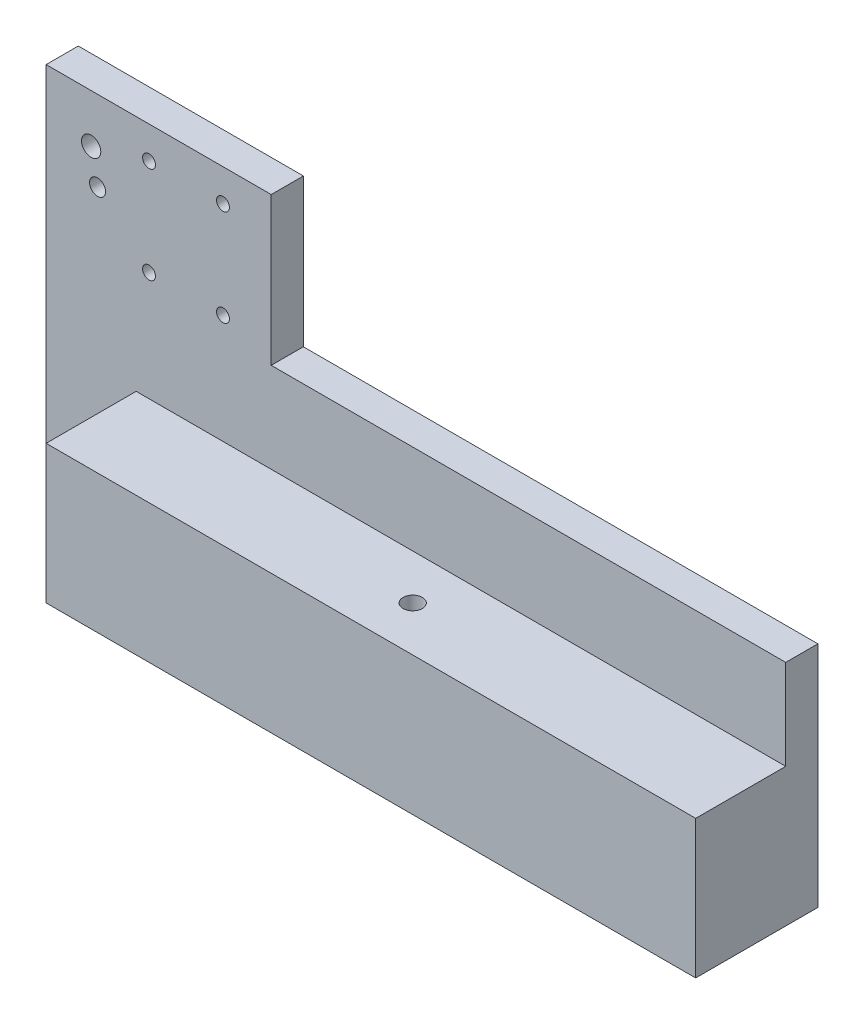
SolidWorks part; units mm, degrees
ref_plane "Ön Düzlem" through (0, 0, 0) normal (0, 0, 1) x (1, 0, 0)
ref_plane "Üst Düzlem" through (0, 0, 0) normal (0, 1, 0) x (1, 0, 0)
ref_plane "Sağ Düzlem" through (0, 0, 0) normal (1, 0, 0) x (0, 0, -1)
sketch "Sketch2" plane through (0, 0, 0) normal (0, 0, 1) x (1, 0, 0)
  line L1 (0, 0) -> (230, 0)
  line L2 (0, 0) -> (0, -120)
  line L3 (0, -120) -> (230, -120)
  line L4 (230, 0) -> (230, -120)
  dimension "D1" = 230
  dimension "D2" = 120
extrude "Boss-Extrude1" add sketch "Sketch2" along normal blind 38
sketch "Sketch3" plane through (0, 0, 38) normal (0, 0, 1) x (1, 0, 0)
  line L0 (28, -120) -> (28, -74)
  line L1 (0, -120) -> (230, -120) construction
  line L2 (28, -74) -> (230, -74)
  line L3 (230, -120) -> (230, 0) construction
  line L5 (0, 0) -> (230, 0)
  line L6 (0, 0) -> (0, -120)
  line L7 (0, -120) -> (28, -120)
  line L8 (230, 0) -> (230, -74)
  dimension "D1" = 46
  dimension "D2" = 28
extrude "Cut-Extrude1" cut sketch "Sketch3" against normal blind 28
sketch "Sketch4" plane through (0, 0, 10) normal (0, 0, 1) x (1, 0, 0)
  line L0 (28, -74) -> (230, -74) construction
  line L1 (230, 0) -> (70, 0)
  line L2 (230, 0) -> (230, -46)
  line L3 (230, -46) -> (70, -46)
  line L4 (70, 0) -> (70, -46)
  line L5 (230, -120) -> (230, -74) construction
  dimension "D1" = 28
  dimension "D2" = 160
extrude "Cut-Extrude2" cut sketch "Sketch4" against normal through all
sketch "Sketch5" plane through (0, 0, 38) normal (0, 0, 1) x (1, 0, 0)
  line L0 (70, 0) -> (0, 0) construction
  line L1 (-45.2028, -117) -> (266.6205, -117)
  line L2 (-45.2028, -117) -> (-45.2028, -145.846)
  line L3 (-45.2028, -145.846) -> (266.6205, -145.846)
  line L4 (266.6205, -117) -> (266.6205, -145.846)
  dimension "D1" = 117
extrude "Cut-Extrude3" cut sketch "Sketch5" against normal blind 72
sketch "Sketch6" plane through (0, -74, 0) normal (0, 1, 0) x (1, 0, 0)
  line L0 (28, -38) -> (230, -38) construction
  line L1 (28, -10) -> (28, -38) construction
  circle A0 centre (128, -24) radius 3
  dimension "D3" = 6
  dimension "D1" = 14
  dimension "D2" = 100
extrude "Cut-Extrude4" cut sketch "Sketch6" against normal blind 15
sketch "Sketch7" plane through (0, 0, 10) normal (0, 0, 1) x (1, 0, 0)
  line L0 (70, 0) -> (0, 0) construction
  line L1 (28, -117) -> (0, -117) construction
  line L2 (0, 0) -> (0, -117) construction
  circle A0 centre (14, -15) radius 3
  circle A1 centre (14, -102) radius 3
  dimension "D2" = 6
  dimension "D3" = 6
  dimension "D5" = 14
  dimension "D1" = 15
  dimension "D4" = 15
  dimension "D6" = 14
extrude "Cut-Extrude5" cut sketch "Sketch7" against normal through all
sketch "Sketch8" plane through (0, 0, 0) normal (0, 0, -1) x (-1, 0, 0)
  line L0 (-70, 0) -> (0, 0) construction
  line L1 (-32, -40) -> (-55, -40) construction
  line L2 (-32, -40) -> (-32, -10) construction
  line L3 (-32, -10) -> (-55, -10) construction
  line L4 (-55, -40) -> (-55, -10) construction
  line L5 (-32, -40) -> (-55, -10) construction
  line L6 (-32, -10) -> (-55, -40) construction
  line L7 (0, 0) -> (0, -117) construction
  circle A0 centre (-55, -10) radius 2
  circle A1 centre (-55, -40) radius 2
  circle A2 centre (-32, -40) radius 2
  circle A3 centre (-32, -10) radius 2
  point P0 (-43.5, -25)
  dimension "D2" = 40
  dimension "D3" = 4
  dimension "D5" = 55
  dimension "D1" = 30
  dimension "D4" = 32
extrude "Cut-Extrude6" cut sketch "Sketch8" against normal through all
sketch "Sketch9" plane through (0, 0, 0) normal (0, 0, -1) x (-1, 0, 0)
  line L0 (-70, 0) -> (0, 0) construction
  line L1 (0, 0) -> (0, -117) construction
  circle A0 centre (-16, -25) radius 2.5
  dimension "D3" = 5
  dimension "D1" = 25
  dimension "D2" = 16
extrude "Cut-Extrude7" cut sketch "Sketch9" against normal through all
